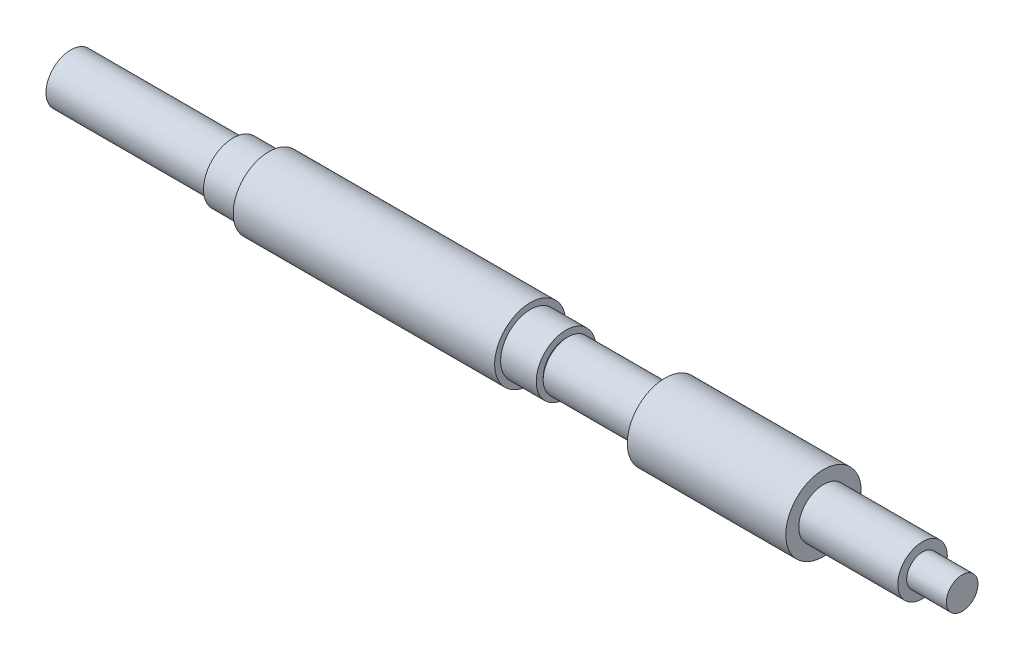
SolidWorks part; units mm, degrees
ref_plane "前视基准面" through (0, 0, 0) normal (0, 0, 1) x (1, 0, 0)
ref_plane "上视基准面" through (0, 0, 0) normal (0, 1, 0) x (1, 0, 0)
ref_plane "右视基准面" through (0, 0, 0) normal (1, 0, 0) x (0, 0, -1)
sketch "草图1" plane through (0, 0, 0) normal (1, 0, 0) x (0, 0, -1)
  circle A0 centre (0, 0) radius 12.5
extrude "凸台-拉伸1" add sketch "草图1" along normal blind 100
sketch "草图2" plane through (100, 0, 0) normal (1, 0, 0) x (0, 0, -1)
  circle A0 centre (0, 0) radius 15
extrude "凸台-拉伸2" add sketch "草图2" against normal blind 18
sketch "草图3" plane through (100, 0, 0) normal (1, 0, 0) x (0, 0, -1)
  circle A0 centre (0, 0) radius 18
extrude "凸台-拉伸3" add sketch "草图3" along normal blind 132
sketch "草图4" plane through (232, 0, 0) normal (1, 0, 0) x (0, 0, -1)
  circle A0 centre (0, 0) radius 15
extrude "凸台-拉伸4" add sketch "草图4" along normal blind 18
sketch "草图5" plane through (250, 0, 0) normal (1, 0, 0) x (0, 0, -1)
  circle A0 centre (0, 0) radius 12.5
extrude "凸台-拉伸5" add sketch "草图5" along normal blind 50
sketch "草图6" plane through (300, 0, 0) normal (1, 0, 0) x (0, 0, -1)
  circle A0 centre (0, 0) radius 19.05
extrude "凸台-拉伸6" add sketch "草图6" along normal blind 80
sketch "草图7" plane through (380, 0, 0) normal (1, 0, 0) x (0, 0, -1)
  circle A0 centre (0, 0) radius 12.5
extrude "凸台-拉伸7" add sketch "草图7" along normal blind 50
sketch "草图9" plane through (430, 0, 0) normal (1, 0, 0) x (0, 0, -1)
  circle A0 centre (0, 0) radius 8
extrude "凸台-拉伸8" add sketch "草图9" along normal blind 20
ref_plane "基准面1" through (300, 0, 0) normal (-1, 0, 0) x (0, 0, 1)
split "分割1" trim tools "基准面1" bodies to split 120 resulting bodies 121 122
sketch "草图11" plane through (82, 0, 0) normal (-1, 0, 0) x (0, 0, 1)
  circle A0 centre (0, 0) radius 11.5
  circle A1 centre (0, 0) radius 12.5
extrude "切除-拉伸2" cut sketch "草图11" along normal blind 1
sketch "草图12" plane through (250, 0, 0) normal (1, 0, 0) x (0, 0, -1)
  circle A0 centre (0, 0) radius 12.5
  circle A1 centre (0, 0) radius 11.5
extrude "切除-拉伸3" cut sketch "草图12" along normal blind 1
